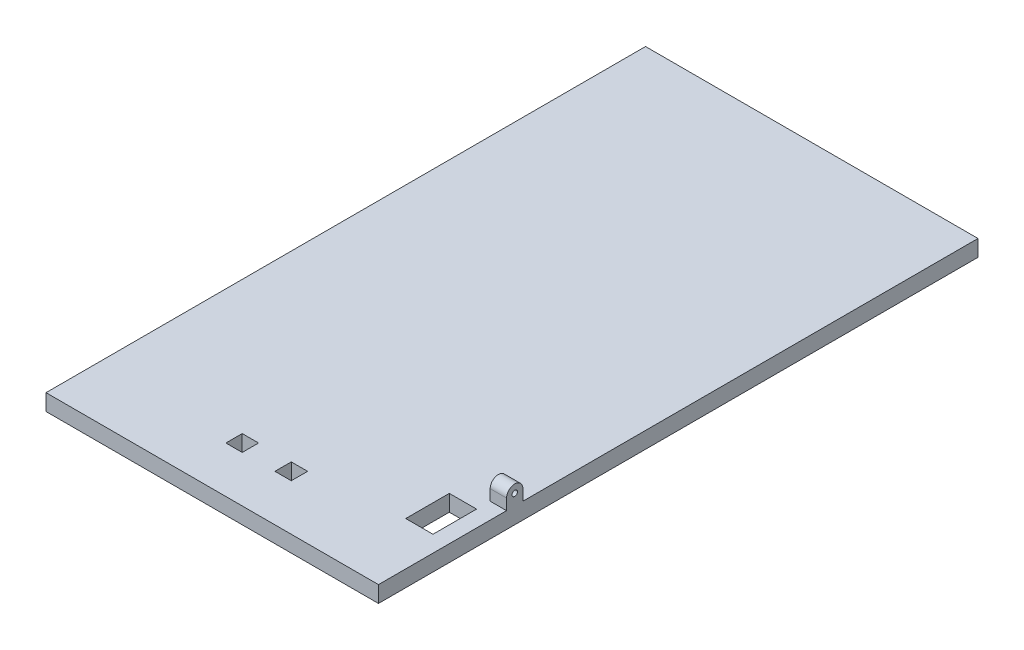
SolidWorks part; units mm, degrees
material "Acrilico TEC"
ref_plane "Front Plane" through (0, 0, 0) normal (0, 0, 1) x (1, 0, 0)
ref_plane "Top Plane" through (0, 0, 0) normal (0, 1, 0) x (1, 0, 0)
ref_plane "Right Plane" through (0, 0, 0) normal (1, 0, 0) x (0, 0, -1)
sketch "Sketch1" plane through (0, 0, 0) normal (0, 1, 0) x (1, 0, 0)
  line L1 (0, 0) -> (61, 0)
  line L2 (0, 0) -> (0, 100)
  line L3 (0, 100) -> (61, 100)
  line L4 (61, 0) -> (61, 100)
  dimension "D1" = 61
  dimension "D2" = 100
extrude "Boss-Extrude1" add sketch "Sketch1" along normal blind 3
ref_plane "Plane1" through (30.5, 0, 0) normal (1, 0, 0) x (0, 0, -1)
ref_plane "Plane2" through (24.5, 0, 0) normal (1, 0, 0) x (0, 0, -1)
sketch "Sketch3" plane through (24.5, 0, 0) normal (1, 0, 0) x (0, 0, -1)
  circle A0 centre (0, 0) radius 1.5
  dimension "D1" = 3
extrude "Boss-Extrude7" add sketch "Sketch3" against normal blind 3
pattern_linear "LPattern1" count 2 spacing 15 along (1, 0, 0) of "Boss-Extrude7"
sketch "Sketch6" plane through (0, 3, 0) normal (0, 1, 0) x (1, 0, 0)
  line L0 (61, 0) -> (61, 100) construction
  line L1 (58, 3) -> (53, 3)
  line L2 (58, 3) -> (58, 11)
  line L3 (58, 11) -> (53, 11)
  line L4 (53, 3) -> (53, 11)
  line L5 (0, 0) -> (61, 0) construction
  dimension "D1" = 5
  dimension "D2" = 3
  dimension "D3" = 3
  dimension "D4" = 8
extrude "Cut-Extrude1" cut sketch "Sketch6" against normal blind 5
sketch "Sketch4" plane through (0, 0, 0) normal (0, 0, 1) x (1, 0, 0)
  line L1 (0, 0) -> (61, 0)
  line L2 (0, 0) -> (0, 3)
  line L3 (0, 3) -> (61, 3)
  line L4 (61, 0) -> (61, 3)
extrude "Boss-Extrude3" add sketch "Sketch4" along normal blind 10
sketch "Sketch8" plane through (61, 0, 0) normal (1, 0, 0) x (0, 0, -1)
  line L9 (13.5, 3) -> (16.5, 3)
  line L10 (16.5, 3) -> (16.5, 5)
  line L12 (13.5, 3) -> (13.5, 5)
  circle A2 centre (15, 5) radius 0.5
  arc A3 (13.5, 5) -> (16.5, 5) centre (15, 5) cw
  dimension "D1" = 3
  dimension "D2" = 15
  dimension "D3" = 1
  dimension "D5" = 1.5
  dimension "D4" = 2
  dimension "D6" = 3
extrude "Boss-Extrude6" add sketch "Sketch8" against normal blind 3
sketch "Sketch9" plane through (0, 0, 0) normal (0, -1, 0) x (1, 0, 0)
  line L0 (30.5, 10) -> (30.5, -77.8967) construction
  line L1 (36.5, 1.5) -> (33.5, 1.5)
  line L2 (36.5, 1.5) -> (36.5, -1.5)
  line L3 (36.5, -1.5) -> (33.5, -1.5)
  line L4 (33.5, 1.5) -> (33.5, -1.5)
  line L5 (0, 10) -> (61, 10) construction
  line L6 (27.5, 1.5) -> (27.5, -1.5)
  line L7 (24.5, -1.5) -> (27.5, -1.5)
  line L8 (24.5, 1.5) -> (24.5, -1.5)
  line L9 (24.5, 1.5) -> (27.5, 1.5)
  dimension "D1" = 3
  dimension "D2" = 3
extrude "Cut-Extrude3" cut sketch "Sketch9" against normal blind 3
